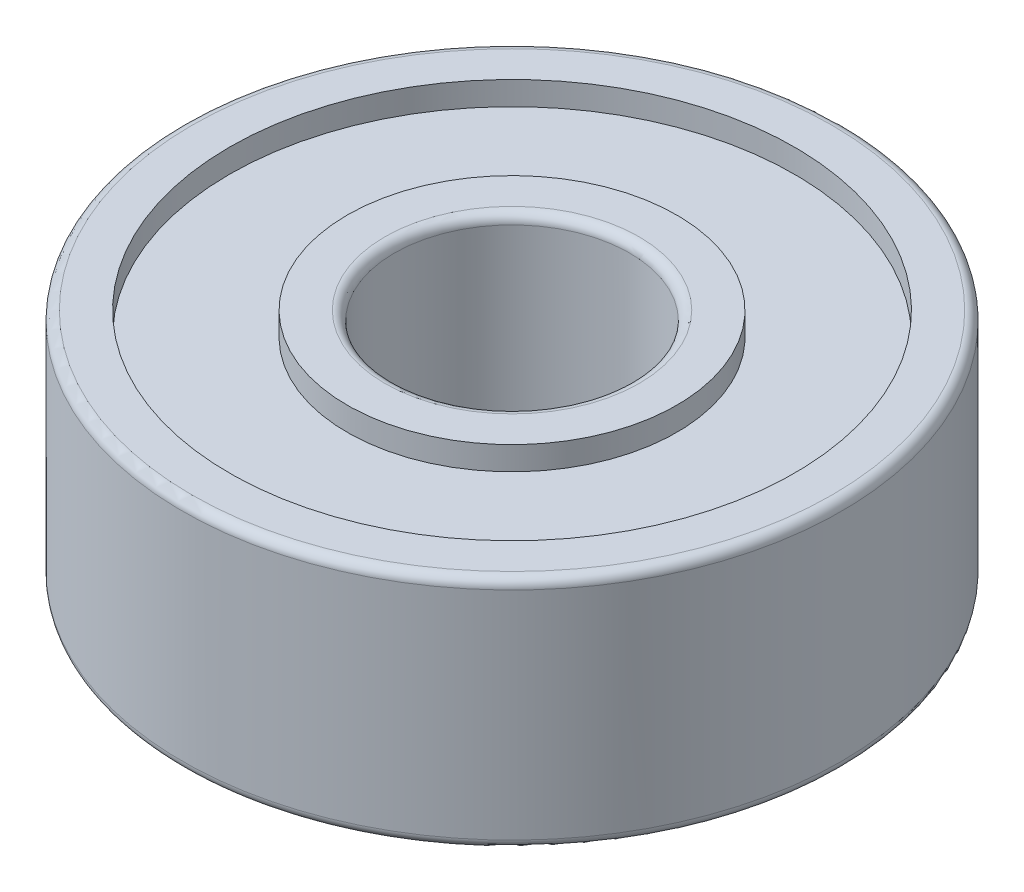
SolidWorks part; units mm, degrees
ref_plane "Front Plane" through (0, 0, 0) normal (0, 0, 1) x (1, 0, 0)
ref_plane "Top Plane" through (0, 0, 0) normal (0, 1, 0) x (1, 0, 0)
ref_plane "Right Plane" through (0, 0, 0) normal (1, 0, 0) x (0, 0, -1)
sketch "Sketch1" plane through (0, 0, 0) normal (0, 0, 1) x (1, 0, 0)
  line L0 (0, 5) -> (0, 0) construction
  line L1 (-2.5, 0) -> (-3.5, 0)
  line L2 (-3.5, 0) -> (-3.5, 0.5)
  line L3 (-3.5, 0.5) -> (-6, 0.5)
  line L4 (-6, 0.5) -> (-6, 0)
  line L5 (-6, 0) -> (-7, 0)
  line L6 (-7, 0) -> (-7, 5)
  line L7 (-7, 5) -> (-6, 5)
  line L8 (-6, 5) -> (-6, 4.5)
  line L9 (-6, 4.5) -> (-3.5, 4.5)
  line L10 (-3.5, 4.5) -> (-3.5, 5)
  line L11 (-3.5, 5) -> (-2.5, 5)
  line L12 (-2.5, 5) -> (-2.5, 0)
  dimension "D1_s" = 5
  dimension "D1._1" = 14
  dimension "MSM_3" = 7
  dimension "MSM_4" = 12
  dimension "B_1" = 5
  dimension "MSM_5" = 4
revolve "Revolve1" add sketch "Sketch1" angle 360 about L0
fillet "Fillet1" radius 0.2 4 edges at (-7, 0, 0) (-7, 5, 0) (-2.5, 0, 0) (-2.5, 5, 0)
